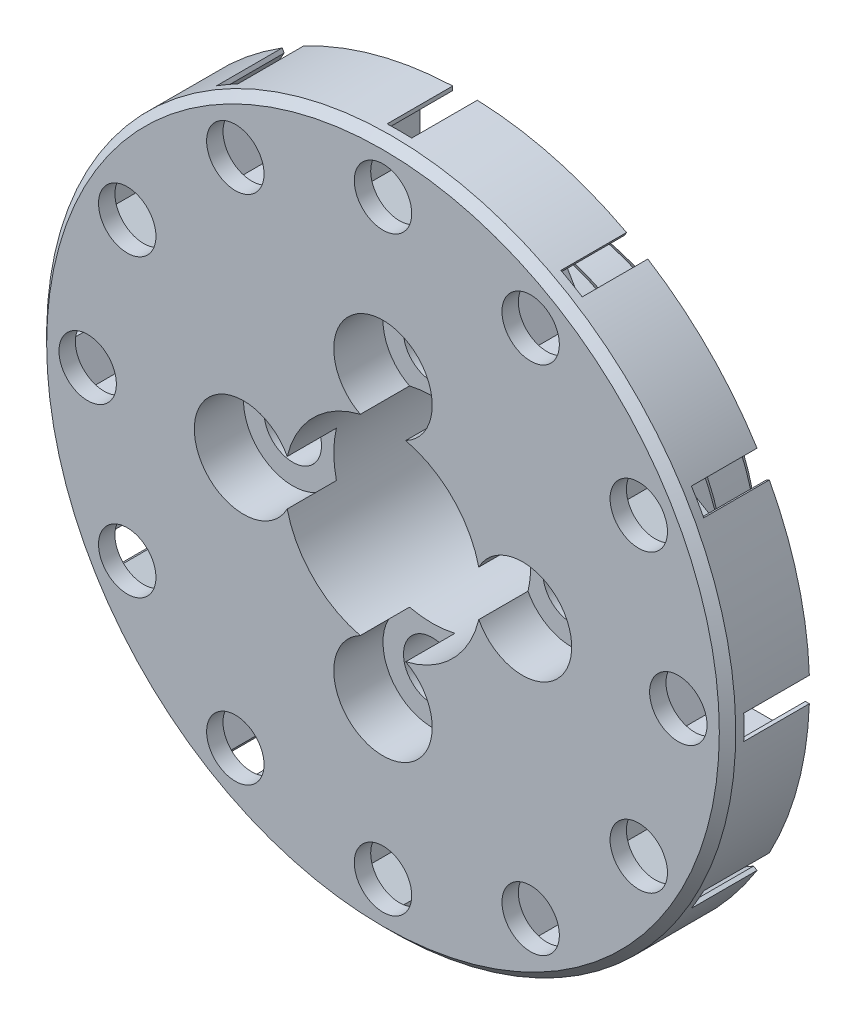
SolidWorks part; units mm, degrees
material "ABS"
ref_plane "Ebene vorne" through (0, 0, 0) normal (0, 0, 1) x (1, 0, 0)
ref_plane "Ebene oben" through (0, 0, 0) normal (0, 1, 0) x (1, 0, 0)
ref_plane "Ebene rechts" through (0, 0, 0) normal (1, 0, 0) x (0, 0, -1)
sketch "Skizze1" plane through (0, 0, 0) normal (1, 0, 0) x (0, 0, -1)
  line L0 (0, 0) -> (58.28, 0) construction
  line L1 (0, 0) -> (0, 21)
  line L2 (0, 21) -> (5, 21)
  line L3 (5, 21) -> (5, 14)
  line L4 (5, 14) -> (7.5, 14)
  line L5 (7.5, 14) -> (7.5, 12.35)
  line L6 (7.5, 12.35) -> (11, 12.35)
  line L7 (11, 12.35) -> (11, 0)
  line L8 (11, 0) -> (0, 0)
  dimension "D1" = 12.35
  dimension "D2" = 14
  dimension "D3" = 21
  dimension "D4" = 5
  dimension "D5" = 2.5
  dimension "D6" = 3.5
revolve "Rotation1" add sketch "Skizze1" angle 360 about L0
sketch "Skizze3" plane through (0, 0, -11) normal (0, 0, -1) x (-1, 0, 0)
  line L0 (0, 0) -> (0, 28.2887) construction
  line L1 (-10.1746, 7) -> (10.1746, 7)
  circle A0 centre (0, 0) radius 12.35 construction
  circle A1 centre (0, 0) radius 12.35 construction
  arc A2 (-10.1746, 7) -> (10.1746, 7) centre (0, 0) cw
  dimension "D1" = 7
sketch "Skizze4" plane through (0, 0, 0) normal (0, 0, 1) x (1, 0, 0)
  line L0 (0, 0) -> (0, 26.3726) construction
  line L1 (0, 0) -> (13.1863, 22.8393) construction
  line L2 (0, 0) -> (22.8393, 13.1863) construction
  line L3 (0, 0) -> (26.3726, 0) construction
  line L4 (0, 0) -> (22.8393, -13.1863) construction
  line L5 (0, 0) -> (13.1863, -22.8393) construction
  line L6 (0, 0) -> (0, -26.3726) construction
  line L7 (0, 0) -> (-13.1863, -22.8393) construction
  line L8 (0, 0) -> (-22.8393, -13.1863) construction
  line L9 (0, 0) -> (-26.3726, 0) construction
  line L10 (0, 0) -> (-22.8393, 13.1863) construction
  line L11 (0, 0) -> (-13.1863, 22.8393) construction
  circle A0 centre (0, 18) radius 1.75
  circle A1 centre (9, 15.5885) radius 1.75
  circle A2 centre (15.5885, 9) radius 1.75
  circle A3 centre (18, 0) radius 1.75
  circle A4 centre (15.5885, -9) radius 1.75
  circle A5 centre (9, -15.5885) radius 1.75
  circle A6 centre (0, -18) radius 1.75
  circle A7 centre (-9, -15.5885) radius 1.75
  circle A8 centre (-15.5885, -9) radius 1.75
  circle A9 centre (-18, 0) radius 1.75
  circle A10 centre (-15.5885, 9) radius 1.75
  circle A11 centre (-9, 15.5885) radius 1.75
  point P41 (0, 0)
  dimension "D1" = 18
  dimension "D2" = 3.5
extrude "Schnitt-Linear austragen2" cut sketch "Skizze4" against normal through all
sketch "Skizze5" plane through (0, 0, -5) normal (0, 0, -1) x (-1, 0, 0)
  line L0 (0, 0) -> (0, 31.9723) construction
  line L8 (7.4123, 12.8385) -> (10.5877, 12.8385)
  line L9 (0, 14.8246) -> (2.75, 16.4123)
  line L15 (2.75, 16.4123) -> (2.75, 19.5877)
  line L21 (2.75, 19.5877) -> (0, 21.1754)
  line L27 (0, 21.1754) -> (-2.75, 19.5877)
  line L33 (-2.75, 19.5877) -> (-2.75, 16.4123)
  line L39 (-2.75, 16.4123) -> (0, 14.8246)
  line L45 (10.5877, 12.8385) -> (12.1754, 15.5885)
  line L51 (12.1754, 15.5885) -> (10.5877, 18.3385)
  line L57 (10.5877, 18.3385) -> (7.4123, 18.3385)
  line L63 (7.4123, 18.3385) -> (5.8246, 15.5885)
  line L69 (5.8246, 15.5885) -> (7.4123, 12.8385)
  line L75 (0, 0) -> (15.9862, 27.6888) construction
  line L76 (12.8385, 7.4123) -> (15.5885, 5.8246)
  line L77 (15.5885, 5.8246) -> (18.3385, 7.4123)
  line L78 (18.3385, 7.4123) -> (18.3385, 10.5877)
  line L79 (18.3385, 10.5877) -> (15.5885, 12.1754)
  line L80 (15.5885, 12.1754) -> (12.8385, 10.5877)
  line L81 (12.8385, 10.5877) -> (12.8385, 7.4123)
  line L82 (0, 0) -> (27.6888, 15.9862) construction
  line L83 (14.8246, 0) -> (16.4123, -2.75)
  line L84 (16.4123, -2.75) -> (19.5877, -2.75)
  line L85 (19.5877, -2.75) -> (21.1754, 0)
  line L86 (21.1754, 0) -> (19.5877, 2.75)
  line L87 (19.5877, 2.75) -> (16.4123, 2.75)
  line L88 (16.4123, 2.75) -> (14.8246, 0)
  line L89 (0, 0) -> (31.9723, 0) construction
  line L90 (12.8385, -7.4123) -> (12.8385, -10.5877)
  line L91 (12.8385, -10.5877) -> (15.5885, -12.1754)
  line L92 (15.5885, -12.1754) -> (18.3385, -10.5877)
  line L93 (18.3385, -10.5877) -> (18.3385, -7.4123)
  line L94 (18.3385, -7.4123) -> (15.5885, -5.8246)
  line L95 (15.5885, -5.8246) -> (12.8385, -7.4123)
  line L96 (0, 0) -> (27.6888, -15.9862) construction
  line L97 (7.4123, -12.8385) -> (5.8246, -15.5885)
  line L98 (5.8246, -15.5885) -> (7.4123, -18.3385)
  line L99 (7.4123, -18.3385) -> (10.5877, -18.3385)
  line L100 (10.5877, -18.3385) -> (12.1754, -15.5885)
  line L101 (12.1754, -15.5885) -> (10.5877, -12.8385)
  line L102 (10.5877, -12.8385) -> (7.4123, -12.8385)
  line L103 (0, 0) -> (15.9862, -27.6888) construction
  line L104 (0, -14.8246) -> (-2.75, -16.4123)
  line L105 (-2.75, -16.4123) -> (-2.75, -19.5877)
  line L106 (-2.75, -19.5877) -> (0, -21.1754)
  line L107 (0, -21.1754) -> (2.75, -19.5877)
  line L108 (2.75, -19.5877) -> (2.75, -16.4123)
  line L109 (2.75, -16.4123) -> (0, -14.8246)
  line L110 (0, 0) -> (0, -31.9723) construction
  line L111 (-7.4123, -12.8385) -> (-10.5877, -12.8385)
  line L112 (-10.5877, -12.8385) -> (-12.1754, -15.5885)
  line L113 (-12.1754, -15.5885) -> (-10.5877, -18.3385)
  line L114 (-10.5877, -18.3385) -> (-7.4123, -18.3385)
  line L115 (-7.4123, -18.3385) -> (-5.8246, -15.5885)
  line L116 (-5.8246, -15.5885) -> (-7.4123, -12.8385)
  line L117 (0, 0) -> (-15.9862, -27.6888) construction
  line L118 (-12.8385, -7.4123) -> (-15.5885, -5.8246)
  line L119 (-15.5885, -5.8246) -> (-18.3385, -7.4123)
  line L120 (-18.3385, -7.4123) -> (-18.3385, -10.5877)
  line L121 (-18.3385, -10.5877) -> (-15.5885, -12.1754)
  line L122 (-15.5885, -12.1754) -> (-12.8385, -10.5877)
  line L123 (-12.8385, -10.5877) -> (-12.8385, -7.4123)
  line L124 (0, 0) -> (-27.6888, -15.9862) construction
  line L125 (-14.8246, 0) -> (-16.4123, 2.75)
  line L126 (-16.4123, 2.75) -> (-19.5877, 2.75)
  line L127 (-19.5877, 2.75) -> (-21.1754, 0)
  line L128 (-21.1754, 0) -> (-19.5877, -2.75)
  line L129 (-19.5877, -2.75) -> (-16.4123, -2.75)
  line L130 (-16.4123, -2.75) -> (-14.8246, 0)
  line L131 (0, 0) -> (-31.9723, 0) construction
  line L132 (-12.8385, 7.4123) -> (-12.8385, 10.5877)
  line L133 (-12.8385, 10.5877) -> (-15.5885, 12.1754)
  line L134 (-15.5885, 12.1754) -> (-18.3385, 10.5877)
  line L135 (-18.3385, 10.5877) -> (-18.3385, 7.4123)
  line L136 (-18.3385, 7.4123) -> (-15.5885, 5.8246)
  line L137 (-15.5885, 5.8246) -> (-12.8385, 7.4123)
  line L138 (0, 0) -> (-27.6888, 15.9862) construction
  line L139 (-7.4123, 12.8385) -> (-5.8246, 15.5885)
  line L140 (-5.8246, 15.5885) -> (-7.4123, 18.3385)
  line L141 (-7.4123, 18.3385) -> (-10.5877, 18.3385)
  line L142 (-10.5877, 18.3385) -> (-12.1754, 15.5885)
  line L143 (-12.1754, 15.5885) -> (-10.5877, 12.8385)
  line L144 (-10.5877, 12.8385) -> (-7.4123, 12.8385)
  line L145 (0, 0) -> (-15.9862, 27.6888) construction
  circle A0 centre (0, 18) radius 2.75 construction
  circle A1 centre (9, 15.5885) radius 2.75 construction
  circle A2 centre (15.5885, 9) radius 2.75 construction
  circle A3 centre (18, 0) radius 2.75 construction
  circle A4 centre (15.5885, -9) radius 2.75 construction
  circle A5 centre (9, -15.5885) radius 2.75 construction
  circle A6 centre (0, -18) radius 2.75 construction
  circle A7 centre (-9, -15.5885) radius 2.75 construction
  circle A8 centre (-15.5885, -9) radius 2.75 construction
  circle A9 centre (-18, 0) radius 2.75 construction
  circle A10 centre (-15.5885, 9) radius 2.75 construction
  circle A11 centre (-9, 15.5885) radius 2.75 construction
  point P115 (0, 0)
  dimension "D1" = 5.5
  dimension "D2" = 12
extrude "Schnitt-Linear austragen3" cut sketch "Skizze5" against normal blind 4
extrude "Schnitt-Linear austragen5" [suppressed] cut sketch "Skizze3" against normal blind 3.5 flip side to cut
sketch "Skizze6" plane through (0, 0, 0) normal (0, 0, 1) x (1, 0, 0)
  line L0 (0, 0) -> (0, 40.4605) construction
  line L1 (0, 0) -> (40.4605, 0) construction
  line L2 (0, 0) -> (0, -40.4605) construction
  line L3 (0, 0) -> (-40.4605, 0) construction
  circle A0 centre (0, 8.5) radius 1.75
  circle A2 centre (8.5, 0) radius 1.75
  circle A3 centre (0, -8.5) radius 1.75
  circle A4 centre (-8.5, 0) radius 1.75
  point P17 (0, 0)
  dimension "D1" = 3.5
  dimension "D2" = 8.5
  dimension "D3" = 4
extrude "Schnitt-Linear austragen6" cut sketch "Skizze6" against normal through all
sketch "Skizze7" plane through (0, 0, 0) normal (0, 0, 1) x (1, 0, 0)
  circle A0 centre (0, 0) radius 13
  dimension "D1" = 26
extrude "Schnitt-Linear austragen7" [suppressed] cut sketch "Skizze7" against normal blind 9
chamfer "Fase1" distance 0.5 angle 45 3 edges at (0, -14, -5) (0, -14, -7.5) (0, -12.35, -11)
chamfer "Fase2" distance 0.5 angle 45 1 edges at (0, -21, 0)
sketch "Skizze8" plane through (0, 0, -5) normal (0, 0, -1) x (-1, 0, 0)
  line L0 (0, 21) -> (0, 0) construction
  line L1 (0.75, 20) -> (-0.75, 20)
  line L2 (0.75, 20) -> (0.75, 22)
  line L3 (0.75, 22) -> (-0.75, 22)
  line L4 (-0.75, 20) -> (-0.75, 22)
  line L5 (0.75, 20) -> (-0.75, 22) construction
  line L6 (0.75, 22) -> (-0.75, 20) construction
  line L7 (10.6495, 16.9455) -> (9.3505, 17.6955)
  line L8 (10.6495, 16.9455) -> (11.6495, 18.6776)
  line L9 (11.6495, 18.6776) -> (10.3505, 19.4276)
  line L10 (9.3505, 17.6955) -> (10.3505, 19.4276)
  line L11 (10.5, 18.1865) -> (0, 0) construction
  line L12 (10.6495, 16.9455) -> (10.3505, 19.4276) construction
  line L13 (11.6495, 18.6776) -> (9.3505, 17.6955) construction
  line L14 (17.6955, 9.3505) -> (16.9455, 10.6495)
  line L15 (17.6955, 9.3505) -> (19.4276, 10.3505)
  line L16 (19.4276, 10.3505) -> (18.6776, 11.6495)
  line L17 (16.9455, 10.6495) -> (18.6776, 11.6495)
  line L18 (18.1865, 10.5) -> (0, 0) construction
  line L19 (17.6955, 9.3505) -> (18.6776, 11.6495) construction
  line L20 (19.4276, 10.3505) -> (16.9455, 10.6495) construction
  line L21 (20, -0.75) -> (20, 0.75)
  line L22 (20, -0.75) -> (22, -0.75)
  line L23 (22, -0.75) -> (22, 0.75)
  line L24 (20, 0.75) -> (22, 0.75)
  line L25 (21, 0) -> (0, 0) construction
  line L26 (20, -0.75) -> (22, 0.75) construction
  line L27 (22, -0.75) -> (20, 0.75) construction
  line L28 (16.9455, -10.6495) -> (17.6955, -9.3505)
  line L29 (16.9455, -10.6495) -> (18.6776, -11.6495)
  line L30 (18.6776, -11.6495) -> (19.4276, -10.3505)
  line L31 (17.6955, -9.3505) -> (19.4276, -10.3505)
  line L32 (18.1865, -10.5) -> (0, 0) construction
  line L33 (16.9455, -10.6495) -> (19.4276, -10.3505) construction
  line L34 (18.6776, -11.6495) -> (17.6955, -9.3505) construction
  line L35 (9.3505, -17.6955) -> (10.6495, -16.9455)
  line L36 (9.3505, -17.6955) -> (10.3505, -19.4276)
  line L37 (10.3505, -19.4276) -> (11.6495, -18.6776)
  line L38 (10.6495, -16.9455) -> (11.6495, -18.6776)
  line L39 (10.5, -18.1865) -> (0, 0) construction
  line L40 (9.3505, -17.6955) -> (11.6495, -18.6776) construction
  line L41 (10.3505, -19.4276) -> (10.6495, -16.9455) construction
  line L42 (-0.75, -20) -> (0.75, -20)
  line L43 (-0.75, -20) -> (-0.75, -22)
  line L44 (-0.75, -22) -> (0.75, -22)
  line L45 (0.75, -20) -> (0.75, -22)
  line L46 (0, -21) -> (0, 0) construction
  line L47 (-0.75, -20) -> (0.75, -22) construction
  line L48 (-0.75, -22) -> (0.75, -20) construction
  line L49 (-10.6495, -16.9455) -> (-9.3505, -17.6955)
  line L50 (-10.6495, -16.9455) -> (-11.6495, -18.6776)
  line L51 (-11.6495, -18.6776) -> (-10.3505, -19.4276)
  line L52 (-9.3505, -17.6955) -> (-10.3505, -19.4276)
  line L53 (-10.5, -18.1865) -> (0, 0) construction
  line L54 (-10.6495, -16.9455) -> (-10.3505, -19.4276) construction
  line L55 (-11.6495, -18.6776) -> (-9.3505, -17.6955) construction
  line L56 (-17.6955, -9.3505) -> (-16.9455, -10.6495)
  line L57 (-17.6955, -9.3505) -> (-19.4276, -10.3505)
  line L58 (-19.4276, -10.3505) -> (-18.6776, -11.6495)
  line L59 (-16.9455, -10.6495) -> (-18.6776, -11.6495)
  line L60 (-18.1865, -10.5) -> (0, 0) construction
  line L61 (-17.6955, -9.3505) -> (-18.6776, -11.6495) construction
  line L62 (-19.4276, -10.3505) -> (-16.9455, -10.6495) construction
  line L63 (-20, 0.75) -> (-20, -0.75)
  line L64 (-20, 0.75) -> (-22, 0.75)
  line L65 (-22, 0.75) -> (-22, -0.75)
  line L66 (-20, -0.75) -> (-22, -0.75)
  line L67 (-21, 0) -> (0, 0) construction
  line L68 (-20, 0.75) -> (-22, -0.75) construction
  line L69 (-22, 0.75) -> (-20, -0.75) construction
  line L70 (-16.9455, 10.6495) -> (-17.6955, 9.3505)
  line L71 (-16.9455, 10.6495) -> (-18.6776, 11.6495)
  line L72 (-18.6776, 11.6495) -> (-19.4276, 10.3505)
  line L73 (-17.6955, 9.3505) -> (-19.4276, 10.3505)
  line L74 (-18.1865, 10.5) -> (0, 0) construction
  line L75 (-16.9455, 10.6495) -> (-19.4276, 10.3505) construction
  line L76 (-18.6776, 11.6495) -> (-17.6955, 9.3505) construction
  line L77 (-9.3505, 17.6955) -> (-10.6495, 16.9455)
  line L78 (-9.3505, 17.6955) -> (-10.3505, 19.4276)
  line L79 (-10.3505, 19.4276) -> (-11.6495, 18.6776)
  line L80 (-10.6495, 16.9455) -> (-11.6495, 18.6776)
  line L81 (-10.5, 18.1865) -> (0, 0) construction
  line L82 (-9.3505, 17.6955) -> (-11.6495, 18.6776) construction
  line L83 (-10.3505, 19.4276) -> (-10.6495, 16.9455) construction
  point P0 (0, 21)
  point P5 (10.5, 18.1865)
  point P19 (18.1865, 10.5)
  point P25 (21, 0)
  point P31 (18.1865, -10.5)
  point P37 (10.5, -18.1865)
  point P43 (0, -21)
  point P49 (-10.5, -18.1865)
  point P55 (-18.1865, -10.5)
  point P61 (-21, 0)
  point P67 (-18.1865, 10.5)
  point P73 (-10.5, 18.1865)
  point P79 (0, 0)
  dimension "D1" = 1.5
  dimension "D2" = 2
  dimension "D4" = 21
  dimension "D3" = 12
extrude "Schnitt-Linear austragen8" cut sketch "Skizze8" against normal up to surface (4 mm away) up to face at (7.25, 15.5885, -1)
sketch "Skizze9" plane through (0, 0, 0) normal (0, 0, 1) x (1, 0, 0)
  circle A0 centre (0, 0) radius 6
  dimension "D1" = 12
extrude "Schnitt-Linear austragen9" cut sketch "Skizze9" against normal through all
sketch "Skizze11" plane through (0, 0, 0) normal (0, 0, 1) x (1, 0, 0)
  line L0 (0, 8.5) -> (0, 0) construction
  line L1 (8.5, 0) -> (0, 0) construction
  line L2 (0, -8.5) -> (0, 0) construction
  line L3 (-8.5, 0) -> (0, 0) construction
  circle A0 centre (0, 8.5) radius 3
  circle A1 centre (8.5, 0) radius 3
  circle A2 centre (0, -8.5) radius 3
  circle A3 centre (-8.5, 0) radius 3
  point P14 (0, 0)
  dimension "D1" = 6
  dimension "D2" = 4
extrude "Schnitt-Linear austragen10" cut sketch "Skizze11" against normal blind 3
